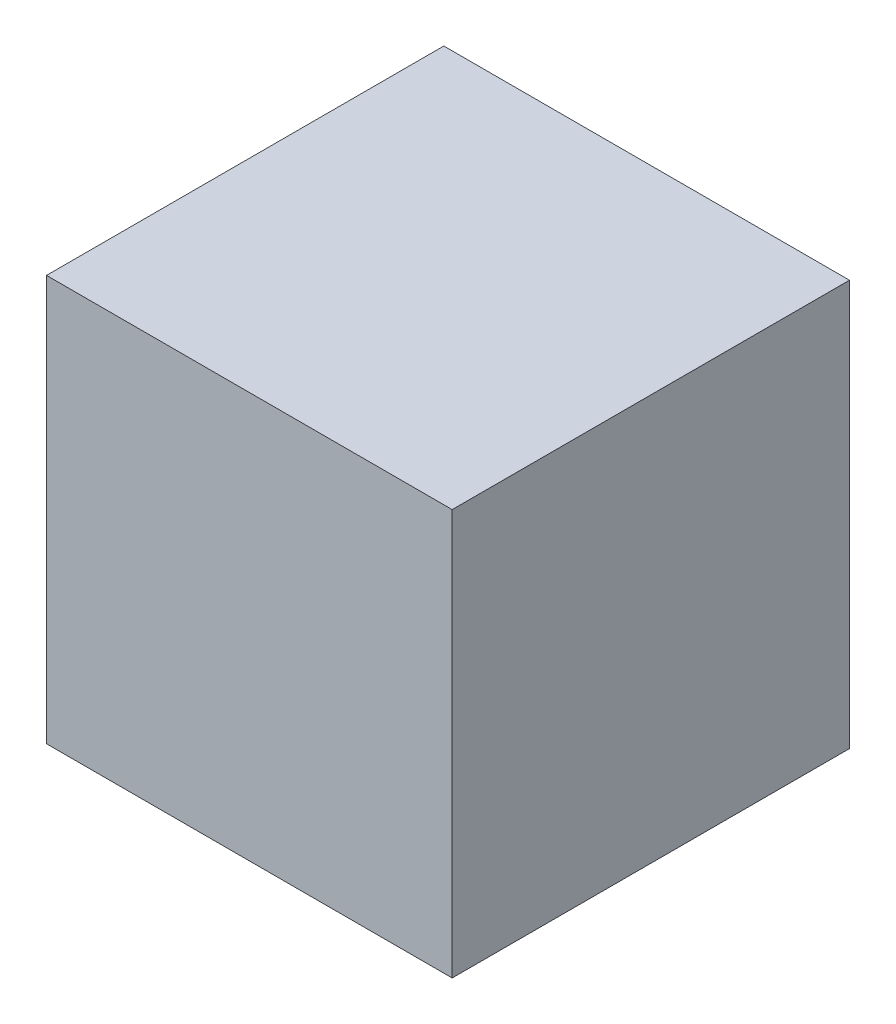
SolidWorks part; units mm, degrees
ref_plane "Front Plane" through (0, 0, 0) normal (0, 0, 1) x (1, 0, 0)
ref_plane "Top Plane" through (0, 0, 0) normal (0, 1, 0) x (1, 0, 0)
ref_plane "Right Plane" through (0, 0, 0) normal (1, 0, 0) x (0, 0, -1)
sketch "Sketch1" plane through (0, 0, 0) normal (0, 1, 0) x (1, 0, 0)
  line L1 (48.5, -47.5) -> (-48.5, -47.5)
  line L2 (48.5, -47.5) -> (48.5, 47.5)
  line L3 (48.5, 47.5) -> (-48.5, 47.5)
  line L4 (-48.5, -47.5) -> (-48.5, 47.5)
  line L5 (48.5, -47.5) -> (-48.5, 47.5) construction
  line L6 (48.5, 47.5) -> (-48.5, -47.5) construction
  point P0 (0, 0)
  dimension "D1" = 97
  dimension "D2" = 95
extrude "Boss-Extrude1" add sketch "Sketch1" along normal mid plane 97
